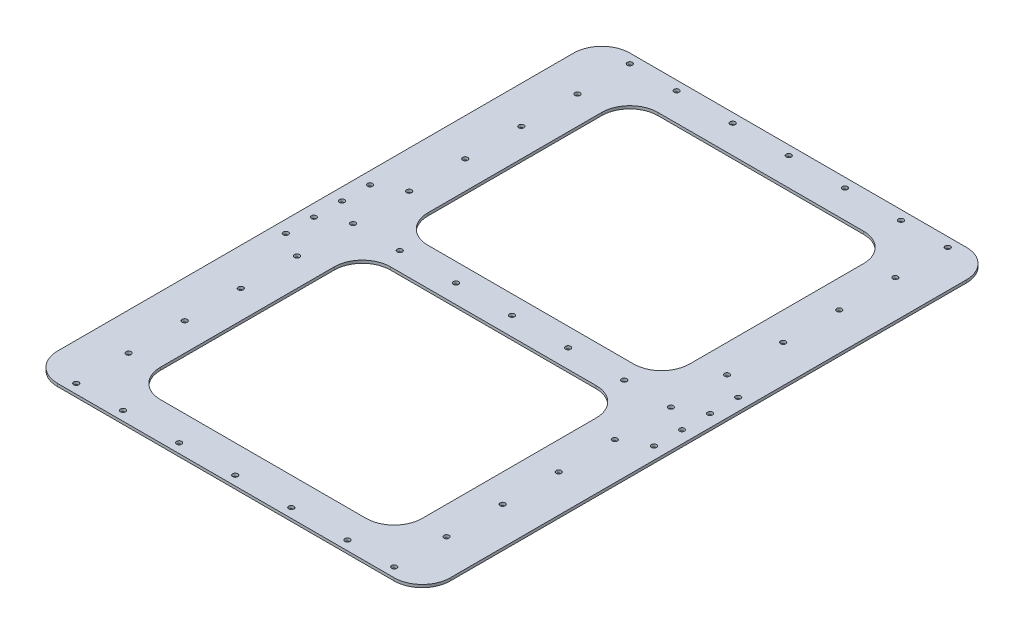
SolidWorks part; units mm, degrees
ref_plane "前视基准面" through (0, 0, 0) normal (0, 0, 1) x (1, 0, 0)
ref_plane "上视基准面" through (0, 0, 0) normal (0, 1, 0) x (1, 0, 0)
ref_plane "右视基准面" through (0, 0, 0) normal (1, 0, 0) x (0, 0, -1)
sketch "Sketch1" plane through (0, 0, 0) normal (0, 1, 0) x (1, 0, 0)
  line L0 (0, 430.9523) -> (0, 0) construction
  line L1 (-210, 306) -> (210, 306)
  line L2 (-210, 306) -> (-210, -306)
  line L3 (-210, -306) -> (210, -306)
  line L4 (210, 306) -> (210, -306)
  line L5 (-210, 306) -> (210, -306) construction
  line L6 (-210, -306) -> (210, 306) construction
  line L13 (0, 0) -> (392.7159, 0) construction
  point P0 (0, 0)
  dimension "D1" = 612
  dimension "D2" = 420
extrude "Boss-Extrude1" add sketch "Sketch1" along normal blind 3
sketch "草图1" plane through (0, 3, 0) normal (0, 1, 0) x (1, 0, 0)
  line L0 (-170, 306) -> (-170, -306) construction
  line L1 (210, 306) -> (-210, 306) construction
  line L2 (-210, -306) -> (210, -306) construction
  line L3 (-210, 306) -> (-210, -306) construction
  line L4 (0, 306) -> (0, -306) construction
  line L5 (-280.0781, 0) -> (279.3653, 0) construction
  line L6 (170, 306) -> (170, -306) construction
  line L7 (-196.85, 306) -> (-196.85, -306) construction
  line L8 (-210, 296) -> (210, 296) construction
  line L9 (210, -306) -> (210, 306) construction
  circle A0 centre (-170, 240) radius 2.75
  circle A1 centre (-170, 180) radius 2.75
  circle A40 centre (-196.85, -15) radius 2.75
  circle A41 centre (-196.85, -45) radius 2.75
  circle A42 centre (-196.85, 45) radius 2.75
  circle A43 centre (-196.85, 15) radius 2.75
  circle A44 centre (196.85, 15) radius 2.75
  circle A45 centre (196.85, 45) radius 2.75
  circle A46 centre (196.85, -45) radius 2.75
  circle A47 centre (196.85, -15) radius 2.75
  circle A48 centre (0, 0) radius 2.75
  circle A49 centre (-60, 0) radius 2.75
  circle A50 centre (-120, 0) radius 2.75
  circle A55 centre (60, 0) radius 2.75
  circle A56 centre (120, 0) radius 2.75
  circle A59 centre (0, 296) radius 2.75
  circle A60 centre (-60, 296) radius 2.75
  circle A61 centre (-120, 296) radius 2.75
  circle A79 centre (-170, 296) radius 2.75
  circle A80 centre (170, 296) radius 2.75
  circle A83 centre (-170, 120) radius 2.75
  circle A84 centre (-170, 60) radius 2.75
  circle A85 centre (-170, 0) radius 2.75
  circle A86 centre (-170, -60) radius 2.75
  circle A87 centre (-170, -120) radius 2.75
  circle A88 centre (-170, -180) radius 2.75
  circle A89 centre (-170, -240) radius 2.75
  circle A90 centre (170, -240) radius 2.75
  circle A91 centre (170, -180) radius 2.75
  circle A92 centre (170, -120) radius 2.75
  circle A93 centre (170, -60) radius 2.75
  circle A94 centre (170, 0) radius 2.75
  circle A95 centre (170, 60) radius 2.75
  circle A96 centre (170, 120) radius 2.75
  circle A97 centre (170, 180) radius 2.75
  circle A98 centre (170, 240) radius 2.75
  circle A99 centre (-180, 296) radius 2.75 [skipped]
  circle A100 centre (60, 296) radius 2.75
  circle A101 centre (120, 296) radius 2.75
  circle A102 centre (120, -296) radius 2.75
  circle A103 centre (60, -296) radius 2.75
  circle A104 centre (170, -296) radius 2.75
  circle A105 centre (-170, -296) radius 2.75
  circle A106 centre (-120, -296) radius 2.75
  circle A107 centre (-60, -296) radius 2.75
  circle A108 centre (0, -296) radius 2.75
  dimension "D2" = 5.5
  dimension "D8" = 5.5
  dimension "D10" = 5.5
  dimension "D15" = 5.5
  dimension "D1" = 40
  dimension "D3" = 60
  dimension "D5" = 13.15
  dimension "D6" = 30
  dimension "D7" = 30
  dimension "D12" = 60
  dimension "D13" = 10
  dimension "D17" = 60
  dimension "D4" = 9
  dimension "D11" = 3
  dimension "D16" = 4
extrude "切除-拉伸1" cut sketch "草图1" against normal through all
sketch "Sketch2" plane through (0, 3, 0) normal (0, 1, 0) x (1, 0, 0)
  line L0 (-350.6408, 0) -> (369.0955, 0) construction
  line L1 (-140, 266) -> (140, 266)
  line L2 (-140, 266) -> (-140, 20)
  line L3 (-140, 20) -> (140, 20)
  line L4 (140, 266) -> (140, 20)
  line L5 (-140, 266) -> (140, 20) construction
  line L6 (-140, 20) -> (140, 266) construction
  line L7 (-140, -20) -> (140, -266) construction
  line L8 (-140, -266) -> (140, -20) construction
  line L9 (140, -266) -> (140, -20)
  line L10 (-140, -20) -> (140, -20)
  line L11 (-140, -266) -> (-140, -20)
  line L12 (-140, -266) -> (140, -266)
  line L13 (210, 306) -> (-210, 306) construction
  point P0 (0, 143)
  point P13 (0, -143)
  dimension "D1" = 20
  dimension "D2" = 40
  dimension "D3" = 280
extrude "Cut-Extrude1" cut sketch "Sketch2" against normal through all both and the other way through all
fillet "Fillet1" radius 30 8 edges at (-140, 1.5, 266) (140, 1.5, 266) (140, 1.5, 20) (-140, 1.5, 20) (-140, 1.5, -20) (140, 1.5, -20) (140, 1.5, -266) (-140, 1.5, -266)
fillet "Fillet2" radius 30 4 edges at (210, 1.5, -306) (210, 1.5, 306) (-210, 1.5, 306) (-210, 1.5, -306)
